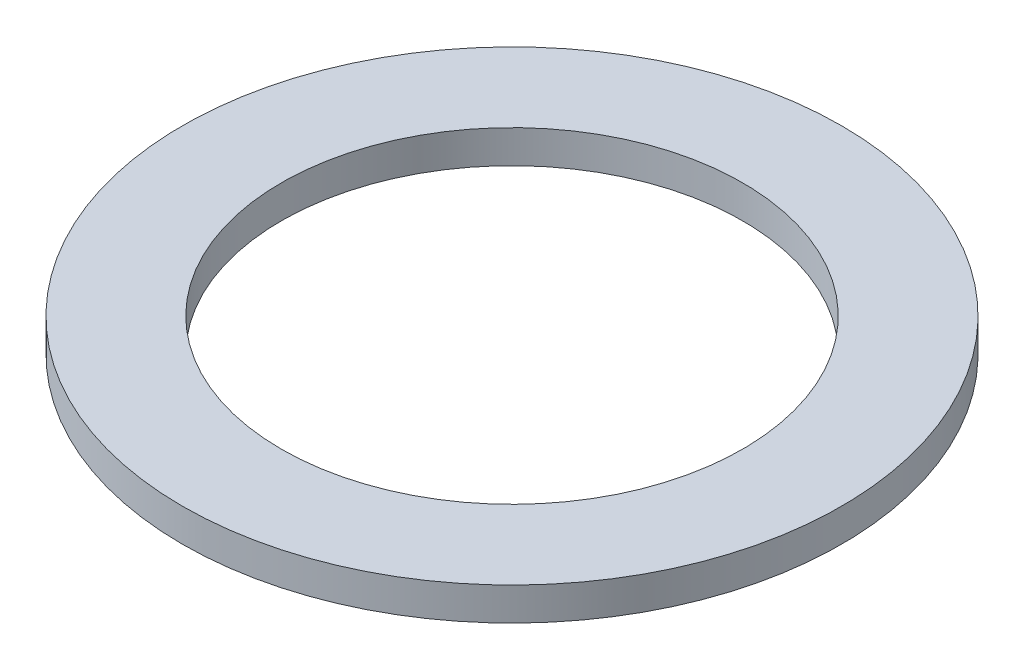
SolidWorks part; units mm, degrees
ref_plane "Front Plane" through (0, 0, 0) normal (0, 0, 1) x (1, 0, 0)
ref_plane "Top Plane" through (0, 0, 0) normal (0, 1, 0) x (1, 0, 0)
ref_plane "Right Plane" through (0, 0, 0) normal (1, 0, 0) x (0, 0, -1)
sketch "Sketch1" plane through (0, 0, 0) normal (0, 1, 0) x (1, 0, 0)
  circle A0 centre (0, 0) radius 4.2
  circle A1 centre (0, 0) radius 6
  dimension "D1" = 8.4
  dimension "D2" = 12
extrude "Boss-Extrude1" add sketch "Sketch1" along normal blind 0.6
